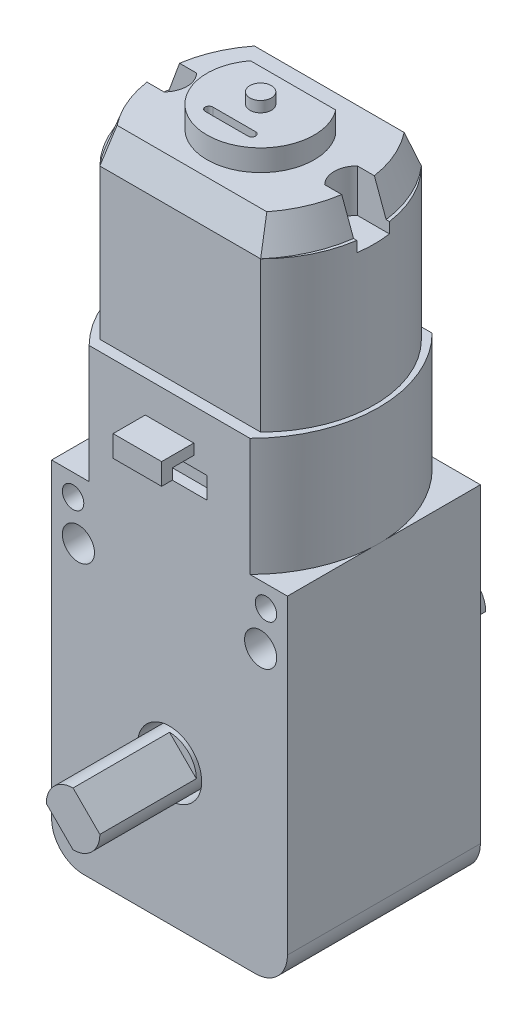
SolidWorks part; units mm, degrees
ref_plane "前视基准面" through (0, 0, 0) normal (0, 0, 1) x (1, 0, 0)
ref_plane "上视基准面" through (0, 0, 0) normal (0, 1, 0) x (1, 0, 0)
ref_plane "右视基准面" through (0, 0, 0) normal (1, 0, 0) x (0, 0, -1)
sketch "草图1" plane through (0, 0, 0) normal (0, 0, 1) x (1, 0, 0)
  line L0 (0, 0) -> (-8, 0)
  line L1 (0, 0) -> (8, 0)
  line L2 (11, 3) -> (11, 32)
  line L3 (11, 32) -> (-11, 32)
  line L4 (-11, 32) -> (-11, 3)
  arc A0 (8, 0) -> (11, 3) centre (8, 3) ccw
  arc A1 (-8, 0) -> (-11, 3) centre (-8, 3) cw
  point P8 (11, 0)
  point P11 (-11, 0)
  dimension "D4" = 3
  dimension "D1" = 11
  dimension "D2" = 11
  dimension "D3" = 32
extrude "凸台-拉伸1" add sketch "草图1" along normal blind 18
sketch "草图2" plane through (0, 32, 0) normal (0, 1, 0) x (1, 0, 0)
  line L0 (0, 0) -> (0, -18) construction
  line L1 (11, -18) -> (-11, -18) construction
  line L2 (7.5, -18) -> (-7.5, -18)
  line L3 (11, -18) -> (11, 0) construction
  line L4 (11, -9) -> (-11, -9) construction
  line L5 (-11, -18) -> (-11, 0) construction
  line L7 (0, -1) -> (-7.5, -1)
  line L8 (0, -1) -> (7.5, -1)
  arc A0 (-7.5, -1) -> (-7.5, -18) centre (1, -9.5) ccw
  arc A1 (7.5, -1) -> (7.5, -18) centre (-1, -9.5) cw
extrude "凸台-拉伸2" add sketch "草图2" along normal blind 11
sketch "草图3" plane through (0, 0, 18) normal (0, 0, 1) x (1, 0, 0)
  circle A0 centre (9, 30) radius 1
  circle A1 centre (8.5, 26.5) radius 1.5
  circle A2 centre (-8.5, 26.5) radius 1.5
  circle A3 centre (-9, 30) radius 1
extrude "切除-拉伸1" cut sketch "草图3" against normal blind 31
sketch "草图4" plane through (0, 0, 18) normal (0, 0, 1) x (1, 0, 0)
  line L0 (0, 0) -> (0, 13) construction
  circle A0 centre (0, 13) radius 3
extrude "切除-拉伸2" cut sketch "草图4" against normal blind 7
sketch "草图5" plane through (0, 0, 0) normal (0, 0, -1) x (-1, 0, 0)
  circle A0 centre (0, 13) radius 3
extrude "切除-拉伸3" cut sketch "草图5" against normal blind 7
sketch "草图6" plane through (0, 0, 11) normal (0, 0, 1) x (1, 0, 0)
  circle A0 centre (0, 13) radius 2.5
extrude "凸台-拉伸3" add sketch "草图6" along normal blind 16
sketch "草图7" plane through (0, 0, 27) normal (0, 0, 1) x (1, 0, 0)
  line L0 (0, 15.5) -> (2.5, 13)
  line L2 (-2.5, 13) -> (0, 10.5)
  circle A0 centre (0, 13) radius 2.5 construction
  circle A1 centre (0, 13) radius 2.5 construction
  arc A2 (0, 15.5) -> (2.5, 13) centre (0, 13) cw
  arc A3 (-2.5, 13) -> (0, 10.5) centre (0, 13) ccw
extrude "切除-拉伸4" cut sketch "草图7" against normal blind 9
sketch "草图8" plane through (0, 0, 7) normal (0, 0, -1) x (-1, 0, 0)
  circle A0 centre (0, 13) radius 2.5
extrude "凸台-拉伸4" add sketch "草图8" along normal blind 16
sketch "草图9" plane through (0, 0, -9) normal (0, 0, -1) x (-1, 0, 0)
  line L0 (0, 15.5) -> (2.5, 13)
  line L2 (-2.5, 13) -> (0, 10.5)
  circle A0 centre (0, 13) radius 2.5 construction
  circle A1 centre (0, 13) radius 2.5 construction
  arc A2 (0, 15.5) -> (2.5, 13) centre (0, 13) cw
  arc A3 (-2.5, 13) -> (0, 10.5) centre (0, 13) ccw
extrude "切除-拉伸5" cut sketch "草图9" against normal blind 9
sketch "草图10" plane through (0, 0, 0) normal (0, -1, 0) x (1, 0, 0)
  line L0 (-8, 0) -> (8, 18) construction
  line L1 (8, 18) -> (-8, 18) construction
  line L2 (-8, 18) -> (8, 0) construction
  line L4 (-2.5, 9) -> (-2.5, 10.5)
  line L5 (-2.5, 10.5) -> (2.5, 10.5)
  line L6 (2.5, 10.5) -> (2.5, 7.5)
  line L7 (2.5, 7.5) -> (-2.5, 7.5)
  line L8 (-2.5, 7.5) -> (-2.5, 9)
extrude "凸台-拉伸5" add sketch "草图10" along normal blind 5
sketch "草图11" plane through (0, 0, 10.5) normal (0, 0, 1) x (1, 0, 0)
  line L0 (-2.5, -5) -> (2.5, 0) construction
  line L1 (2.5, 0) -> (-2.5, 0) construction
  line L2 (-2.5, 0) -> (2.5, -5) construction
  circle A0 centre (0, -2.5) radius 1
extrude "切除-拉伸6" cut sketch "草图11" against normal blind 14
sketch "草图12" plane through (0, 0, 0) normal (0, 0, -1) x (-1, 0, 0)
  line L0 (0, 0) -> (0, 22) construction
  circle A0 centre (0, 22) radius 2
extrude "凸台-拉伸6" add sketch "草图12" along normal blind 2
sketch "草图13" plane through (0, 0, 0) normal (0, 0, -1) x (-1, 0, 0)
  line L0 (0, 32) -> (0, 24.8245) construction
  line L1 (-11, 32) -> (11, 32) construction
  circle A0 centre (-6.6468, 28.8812) radius 2
  circle A1 centre (6.6468, 28.8812) radius 2
extrude "切除-拉伸7" cut sketch "草图13" against normal blind 5
sketch "草图14" plane through (0, 0, 5) normal (0, 0, -1) x (-1, 0, 0)
  line L0 (0, 32) -> (0, 26.9247) construction
  line L1 (-11, 32) -> (11, 32) construction
  circle A0 centre (-6.6468, 28.8812) radius 1.4
  arc A1 (-8.6381, 29.0678) -> (-8.4416, 27.9989) centre (-6.6468, 28.8812) ccw
  arc A2 (-8.0485, 30.3078) -> (-8.6381, 29.0678) centre (-9, 30) cw
  arc A3 (-8.4416, 27.9989) -> (-7.0614, 26.9247) centre (-8.5, 26.5) cw
  arc A4 (-7.0614, 26.9247) -> (-8.0485, 30.3078) centre (-6.6468, 28.8812) ccw
  arc A5 (7.0614, 26.9247) -> (8.0485, 30.3078) centre (6.6468, 28.8812) cw
  arc A6 (8.4416, 27.9989) -> (7.0614, 26.9247) centre (8.5, 26.5) ccw
  arc A7 (8.0485, 30.3078) -> (8.6381, 29.0678) centre (9, 30) ccw
  arc A8 (8.6381, 29.0678) -> (8.4416, 27.9989) centre (6.6468, 28.8812) cw
  circle A9 centre (6.6468, 28.8812) radius 1.4
extrude "凸台-拉伸8" add sketch "草图14" along normal blind 3
cosmetic thread "装饰螺纹线1" parameters "D2"=8.4
cosmetic thread "装饰螺纹线2" parameters "D2"=8.4
sketch "草图16" plane through (0, 0, 1) normal (0, 0, -1) x (-1, 0, 0)
  line L0 (0, 32) -> (0, 36) construction
  line L1 (-11, 32) -> (11, 32) construction
  line L2 (0, 36) -> (3.5, 36)
  line L3 (0, 36) -> (-3.5, 36)
  line L4 (-3.5, 36) -> (-3.5, 38)
  line L5 (-3.5, 38) -> (3.5, 38)
  line L6 (3.5, 38) -> (3.5, 36)
extrude "切除-拉伸8" cut sketch "草图16" against normal blind 22
sketch "草图17" plane through (0, 43, 0) normal (0, 1, 0) x (1, 0, 0)
  line L0 (4.2096, -1) -> (4.2096, -2) construction
  line L1 (7.5, -1) -> (-7.5, -1) construction
  line L2 (7.5, -2) -> (-7.5, -2)
  line L4 (-7.5, -17) -> (7.5, -17)
  arc A0 (7.5, -2) -> (7.5, -17) centre (0, -9.5) cw
  arc A1 (-7.5, -2) -> (-7.5, -17) centre (0, -9.5) ccw
extrude "切除-拉伸9" cut sketch "草图17" against normal blind 11
sketch "草图18" plane through (0, 0, 1) normal (0, 0, -1) x (-1, 0, 0)
  line L0 (2.2623, 38) -> (2.2623, 40)
  line L1 (3.5, 38) -> (-3.5, 38) construction
  line L2 (-2.2623, 40) -> (2.2623, 40)
  line L3 (0, 36) -> (0, 42.447) construction
  line L4 (-3.5, 36) -> (3.5, 36) construction
  line L5 (-2.2623, 38) -> (-2.2623, 40)
  line L6 (-2.2623, 38) -> (2.2623, 38)
  point P12 (0, 40)
extrude "凸台-拉伸9" add sketch "草图18" along normal blind 3
sketch "草图19" plane through (2.2623, 0, 0) normal (1, 0, 0) x (0, 0, -1)
  line L0 (2, 38) -> (1, 38)
  line L1 (2, 38) -> (-1, 38) construction
  line L2 (1, 38) -> (1, 39)
  line L3 (1, 39) -> (-1, 39)
  line L4 (-1, 40) -> (-1, 38) construction
  line L5 (-1, 39) -> (-1, 38)
  line L6 (-1, 38) -> (1, 38)
extrude "切除-拉伸10" cut sketch "草图19" against normal blind 8 contours L2 L3 L5 L6
ref_plane "基准面1" through (0, 0, 9.5) normal (0, 0, 1) x (1, 0, 0)
mirror "镜向2" about plane through (0, 0, 9.5) normal (0, 0, 1) of "凸台-拉伸9"
sketch "草图20" plane through (-2.2623, 0, 0) normal (-1, 0, 0) x (0, 0, 1)
  line L0 (21, 38) -> (20, 38)
  line L1 (21, 38) -> (18, 38) construction
  line L2 (20, 38) -> (20, 39)
  line L3 (20, 39) -> (18, 39)
  line L4 (18, 38) -> (18, 40) construction
  line L5 (18, 39) -> (18, 38)
  line L6 (18, 38) -> (20, 38)
extrude "切除-拉伸11" cut sketch "草图20" against normal blind 8 contours L2 L3 L5 L6
sketch "草图21" plane through (0, 32, 0) normal (0, 1, 0) x (1, 0, 0)
  line L0 (7.5, -2) -> (-7.5, -2)
  line L2 (-7.5, -17) -> (7.5, -17)
  arc A0 (7.5, -2) -> (7.5, -17) centre (0, -9.5) cw
  arc A1 (-7.5, -2) -> (-7.5, -17) centre (0, -9.5) ccw
extrude "凸台-拉伸10" add sketch "草图21" along normal blind 25
sketch "草图22" plane through (0, 57, 0) normal (0, 1, 0) x (1, 0, 0)
  line L0 (10.6066, -9.5) -> (-13.6471, -9.5) construction
  line L1 (-10.4969, -7.9787) -> (-7.4969, -7.9787)
  line L2 (-7.4969, -7.9787) -> (-7.4969, -11.0213)
  line L3 (-10.4969, -11.0213) -> (-7.4969, -11.0213)
  line L4 (0, -2) -> (0, -17) construction
  line L5 (7.5, -2) -> (-7.5, -2) construction
  line L6 (-7.5, -17) -> (7.5, -17) construction
  line L7 (10.4969, -11.0213) -> (7.4969, -11.0213)
  line L8 (7.4969, -7.9787) -> (7.4969, -11.0213)
  line L9 (10.4969, -7.9787) -> (7.4969, -7.9787)
  arc A0 (7.5, -17) -> (7.5, -2) centre (0, -9.5) ccw construction
  arc A1 (-7.5, -2) -> (-7.5, -17) centre (0, -9.5) ccw construction
  arc A2 (-10.4969, -7.9787) -> (-10.4969, -11.0213) centre (0, -9.5) ccw
  arc A3 (10.4969, -7.9787) -> (10.4969, -11.0213) centre (0, -9.5) cw
  point P14 (-7.4969, -9.5)
sketch "草图23" plane through (0, 57, 0) normal (0, 1, 0) x (1, 0, 0)
  line L0 (-10.4969, -7.9787) -> (-7.4969, -7.9787)
  line L1 (0, -2) -> (0, -17) construction
  line L2 (-7.4969, -11.0213) -> (-10.4969, -11.0213)
  line L3 (7.4969, -11.0213) -> (10.4969, -11.0213)
  line L4 (10.4969, -7.9787) -> (7.4969, -7.9787)
  arc A0 (-10.4969, -7.9787) -> (-10.4969, -11.0213) centre (0, -9.5) ccw
  arc A1 (-7.4969, -7.9787) -> (-7.4969, -11.0213) centre (-9.0182, -9.5) cw
  arc A2 (7.4969, -7.9787) -> (7.4969, -11.0213) centre (9.0182, -9.5) ccw
  arc A3 (10.4969, -7.9787) -> (10.4969, -11.0213) centre (0, -9.5) cw
extrude "切除-拉伸13" cut sketch "草图23" against normal blind 1
sketch "草图24" plane through (0, 57, 0) normal (0, 1, 0) x (1, 0, 0)
  line L0 (7.5, -2) -> (-7.5, -2)
  line L2 (-7.5, -17) -> (7.5, -17)
  arc A0 (7.5, -2) -> (7.5, -17) centre (-1.1863, -9.5) cw
  arc A1 (-7.5, -2) -> (-7.5, -17) centre (1.1863, -9.5) ccw
extrude "凸台-拉伸11" add sketch "草图24" along normal blind 3 draft 20
sketch "草图25" plane through (0, 60, 0) normal (0, 1, 0) x (1, 0, 0)
  line L0 (0, -3.0919) -> (0, -15.9081) construction
  line L1 (6.9849, -3.0919) -> (-6.9849, -3.0919) construction
  line L2 (-6.9849, -15.9081) -> (6.9849, -15.9081) construction
  line L4 (9.1979, -9.5) -> (-9.1979, -9.5) construction
  arc A0 (6.9849, -15.9081) -> (6.9849, -3.0919) centre (-1.1863, -9.5) ccw construction
  arc A1 (-6.9849, -3.0919) -> (-6.9849, -15.9081) centre (1.1863, -9.5) ccw construction
  circle A2 centre (0, -9.5) radius 5
extrude "凸台-拉伸12" add sketch "草图25" along normal blind 2
sketch "草图26" plane through (0, 62, 0) normal (0, 1, 0) x (1, 0, 0)
  line L0 (3.978, -6.4708) -> (-3.978, -6.4708)
  circle A0 centre (0, -9.5) radius 5 construction
  arc A1 (3.978, -6.4708) -> (-3.978, -6.4708) centre (0, -9.5) ccw
extrude "切除-拉伸14" cut sketch "草图26" against normal blind 2
sketch "草图30" plane through (0, 57, 0) normal (0, -1, 0) x (1, 0, 0)
  line L0 (7.4969, 7.9787) -> (10.4969, 7.9787)
  line L1 (10.4969, 7.9787) -> (10.4969, 11.0213)
  line L2 (10.4969, 11.0213) -> (7.4969, 11.0213)
  line L3 (0, 3.0919) -> (0, 18.7115) construction
  line L4 (6.9849, 3.0919) -> (-6.9849, 3.0919) construction
  line L5 (-10.4969, 11.0213) -> (-7.4969, 11.0213)
  line L6 (-10.4969, 7.9787) -> (-10.4969, 11.0213)
  line L7 (-7.4969, 7.9787) -> (-10.4969, 7.9787)
  arc A0 (7.4969, 7.9787) -> (7.4969, 11.0213) centre (9.0182, 9.5) cw
  arc A1 (-7.4969, 7.9787) -> (-7.4969, 11.0213) centre (-9.0182, 9.5) ccw
extrude "切除-拉伸15" cut sketch "草图30" against normal blind 14
sketch "草图31" plane through (0, 62, 0) normal (0, 1, 0) x (1, 0, 0)
  line L5 (2, -12.6741) -> (-2, -12.6741)
  line L6 (2, -11.9646) -> (-2, -11.9646)
  arc A1 (2, -12.6741) -> (2, -11.9646) centre (2, -12.3193) ccw
  arc A2 (-2, -11.9646) -> (-2, -12.6741) centre (-2, -12.3193) ccw
  point P7 (0, -12.3193)
extrude "切除-拉伸16" cut sketch "草图31" against normal blind 14
sketch "草图32" plane through (0, 62, 0) normal (0, 1, 0) x (1, 0, 0)
  line L0 (0, -14.5) -> (0, -9.5) construction
  arc A0 (-3.978, -6.4708) -> (3.978, -6.4708) centre (0, -9.5) ccw construction
  circle A1 centre (0, -9.5) radius 1
extrude "凸台-拉伸13" add sketch "草图32" along normal blind 1
